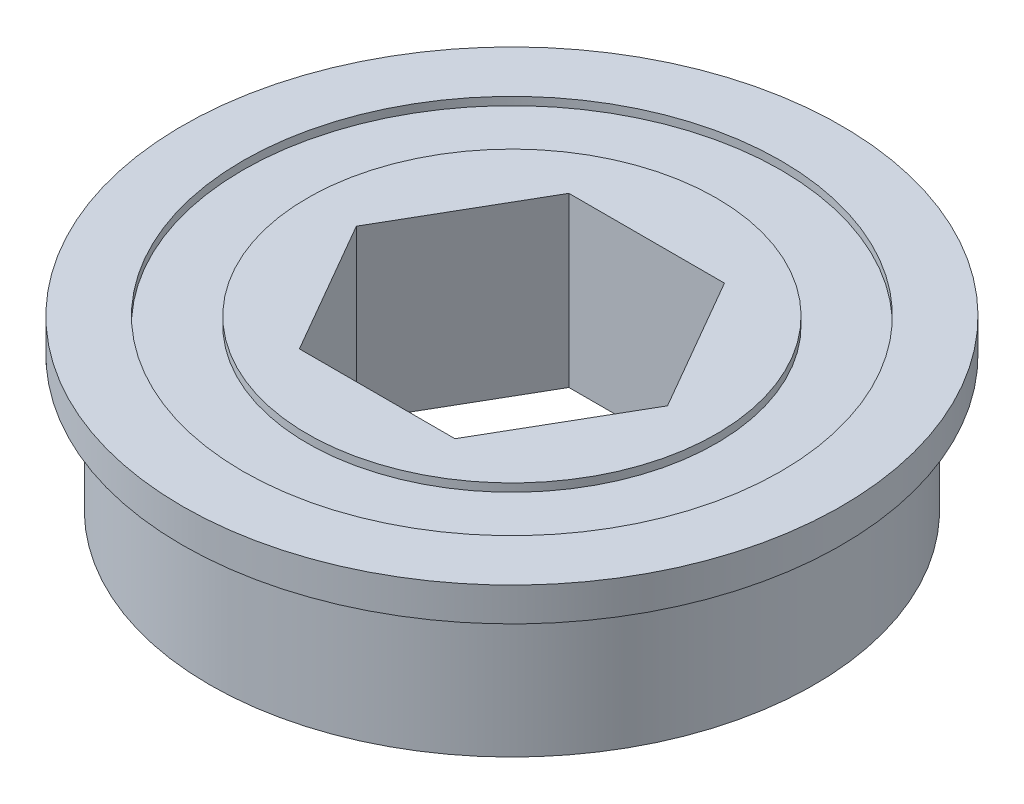
SolidWorks part; units mm, degrees
material "Plain Carbon Steel"
ref_plane "Front Plane" through (0, 0, 0) normal (0, 0, 1) x (1, 0, 0)
ref_plane "Top Plane" through (0, 0, 0) normal (0, 1, 0) x (1, 0, 0)
ref_plane "Right Plane" through (0, 0, 0) normal (1, 0, 0) x (0, 0, -1)
sketch "Sketch1" plane through (0, 0, 0) normal (0, 0, 1) x (1, 0, 0)
  line L0 (-14.2748, 0) -> (0, 0)
  line L1 (0, 0) -> (0, 7.9375)
  line L2 (0, 7.9375) -> (-15.5575, 7.9375)
  line L3 (-15.5575, 7.9375) -> (-15.5575, 6.35)
  line L4 (-15.5575, 6.35) -> (-14.2748, 6.35)
  line L5 (-14.0583, 5.975) -> (-14.2748, 5.6)
  line L6 (-14.2748, 5.6) -> (-14.2748, 0)
  line L7 (0, 0) -> (0, 7.9375) construction
  line L8 (0, 0) -> (0, -11.7452) construction
  arc A0 (-14.2748, 6.35) -> (-14.0583, 5.975) centre (-14.2748, 6.1) cw
  dimension "D6" = 0.25
  dimension "D1" = 5.6
  dimension "D2" = 28.5496
  dimension "D3" = 15.5575
  dimension "D4" = 7.9375
  dimension "D5" = 150
  dimension "D7" = 1.5875
revolve "Revolve1" add sketch "Sketch1" angle 360 about L7
sketch "Sketch3" plane through (0, 0, 0) normal (0, -1, 0) x (1, 0, 0)
  circle A0 centre (0, 0) radius 12.7
  circle A1 centre (0, 0) radius 9.652
  point P3 (0, 0)
  dimension "D1" = 25.4
  dimension "D2" = 19.304
extrude "Cut-Extrude1" cut sketch "Sketch3" against normal blind 0.381
sketch "Sketch4" plane through (0, 0, 0) normal (0, -1, 0) x (1, 0, 0)
  line L1 (-7.3439, 0) -> (-3.6719, -6.36)
  line L2 (-3.6719, -6.36) -> (3.6719, -6.36)
  line L3 (3.6719, -6.36) -> (7.3439, 0)
  line L4 (7.3439, 0) -> (3.6719, 6.36)
  line L5 (3.6719, 6.36) -> (-3.6719, 6.36)
  line L6 (-3.6719, 6.36) -> (-7.3439, 0)
  circle A0 centre (0, 0) radius 6.36 construction
  point P1 (0, 0)
  dimension "D1" = 12.72
extrude "Cut-Extrude2" cut sketch "Sketch4" against normal through all
sketch "Sketch5" plane through (0, 7.9375, 0) normal (0, 1, 0) x (-1, 0, 0)
  circle A0 centre (0, 0) radius 9.652
  circle A1 centre (0, 0) radius 12.7
  point P3 (0, 0)
  dimension "D1" = 25.4
  dimension "D2" = 19.304
extrude "Cut-Extrude3" cut sketch "Sketch5" against normal blind 0.381
